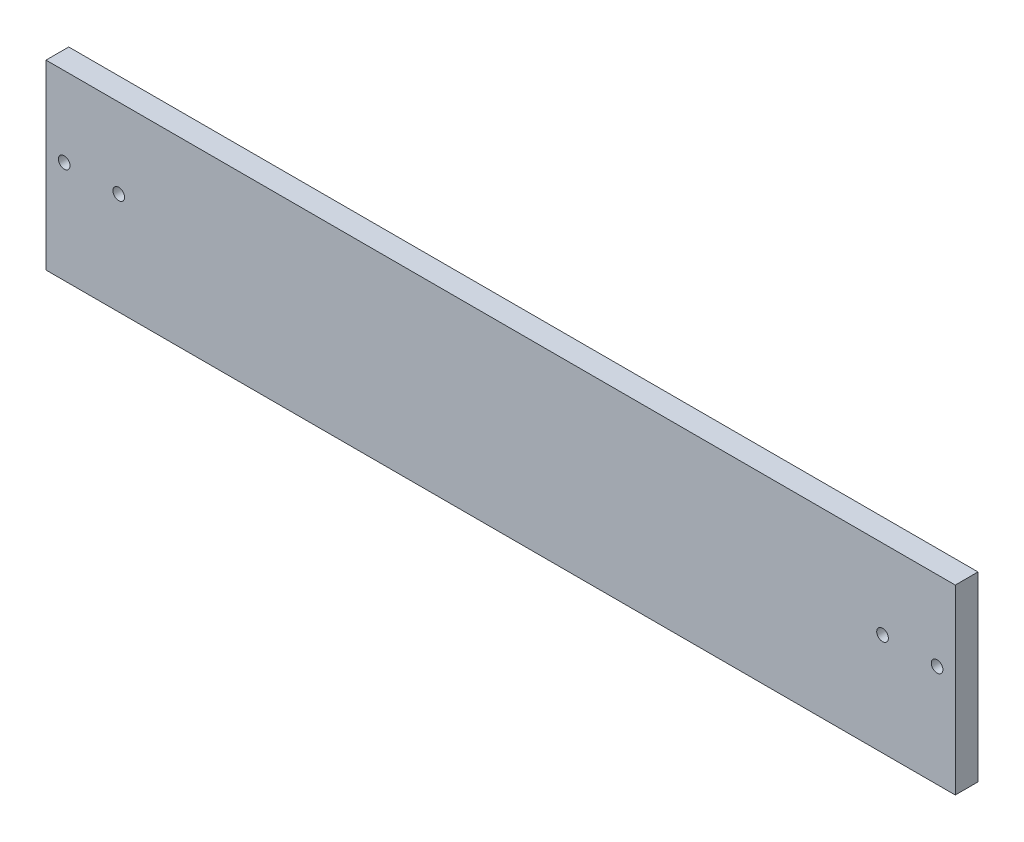
SolidWorks part; units mm, degrees
ref_plane "Front Plane" through (0, 0, 0) normal (0, 0, 1) x (1, 0, 0)
ref_plane "Top Plane" through (0, 0, 0) normal (0, 1, 0) x (1, 0, 0)
ref_plane "Right Plane" through (0, 0, 0) normal (1, 0, 0) x (0, 0, -1)
sketch "Sketch1" plane through (0, 0, 0) normal (0, 0, 1) x (1, 0, 0)
  line L1 (-127, 25.4) -> (127, 25.4)
  line L2 (-127, 25.4) -> (-127, -25.4)
  line L3 (-127, -25.4) -> (127, -25.4)
  line L4 (127, 25.4) -> (127, -25.4)
  line L5 (-127, 25.4) -> (127, -25.4) construction
  line L6 (-127, -25.4) -> (127, 25.4) construction
  point P0 (0, 0)
  dimension "D1" = 254
  dimension "D2" = 50.8
extrude "Boss-Extrude1" add sketch "Sketch1" along normal blind 6.35
sketch "Sketch2" plane through (0, 0, 6.35) normal (0, 0, 1) x (1, 0, 0)
  line L0 (-101.6, 2.3799) -> (-106.68, 2.3799) construction
  line L1 (-127, 25.4) -> (-101.6, 25.4) construction
  line L2 (-127, 25.4) -> (-127, 0) construction
  line L3 (-127, 0) -> (-101.6, 0) construction
  line L4 (-101.6, 25.4) -> (-101.6, 0) construction
  line L5 (-106.68, 25.4) -> (-106.68, 3.175) construction
  line L7 (-127, 2.3799) -> (-121.92, 2.3799) construction
  line L9 (-121.92, 25.4) -> (-121.92, 3.175) construction
  line L10 (0, 0) -> (0, -25.4) construction
  line L11 (-127, -25.4) -> (127, -25.4) construction
  line L12 (0, -25.4) -> (0, 25.4) construction
  line L13 (127, 25.4) -> (-127, 25.4) construction
  point P8 (-106.68, 3.175)
  point P15 (-121.92, 3.175)
  dimension "D1" = 25.4
  dimension "D2" = 25.4
  dimension "D3" = 5.08
  dimension "D4" = 22.225
  dimension "D5" = 5.08
hole_wizard "#4 Clearance Hole1" positions "Sketch2" profile "Sketch3" hole size "#4" standard "ANSI Inch" end condition through all
sketch "Sketch3" plane through (-121.92, 3.175, 6.35) normal (1, 0, 0) x (0, -1, 0)
  line L0 (0, 0) -> (0, 6.35)
  line L1 (0, 6.35) -> (1.6256, 6.35)
  line L2 (1.6256, 6.35) -> (1.6256, 0)
  line L5 (1.6256, 0) -> (0, 0)
  line L11 (0, -6.35) -> (0, 107.95) construction
  dimension "Thru Hole Dia." = 3.2512
  dimension "Thru Hole Depth" = 6.35
sketch "Sketch4" plane through (0, 0, 6.35) normal (0, 0, 1) x (1, 0, 0)
  line L0 (0, 25.4) -> (0, -25.4) construction
  line L1 (127, 25.4) -> (-127, 25.4) construction
  line L2 (-127, -25.4) -> (127, -25.4) construction
  line L3 (127, 7.5617) -> (121.92, 7.5617) construction
  line L4 (127, 25.4) -> (101.6, 25.4)
  line L5 (127, 25.4) -> (127, 0)
  line L6 (127, 0) -> (101.6, 0)
  line L7 (101.6, 25.4) -> (101.6, 0)
  line L8 (101.6, 7.5617) -> (106.68, 7.5617) construction
  line L9 (106.68, 25.4) -> (106.68, 3.175) construction
  line L10 (121.92, 25.4) -> (121.92, 3.175) construction
  point P16 (106.68, 3.175)
  point P18 (121.92, 3.175)
  dimension "D1" = 25.4
  dimension "D2" = 25.4
  dimension "D3" = 5.08
  dimension "D4" = 5.08
  dimension "D5" = 22.225
hole_wizard "#4 Clearance Hole2" positions "Sketch4" profile "Sketch5" hole size "#4" standard "ANSI Inch" end condition through all
sketch "Sketch5" plane through (121.92, 3.175, 6.35) normal (1, 0, 0) x (0, -1, 0)
  line L0 (0, 0) -> (0, 6.35)
  line L1 (0, 6.35) -> (1.6256, 6.35)
  line L2 (1.6256, 6.35) -> (1.6256, 0)
  line L5 (1.6256, 0) -> (0, 0)
  line L11 (0, -6.35) -> (0, 107.95) construction
  dimension "Thru Hole Dia." = 3.2512
  dimension "Thru Hole Depth" = 6.35
